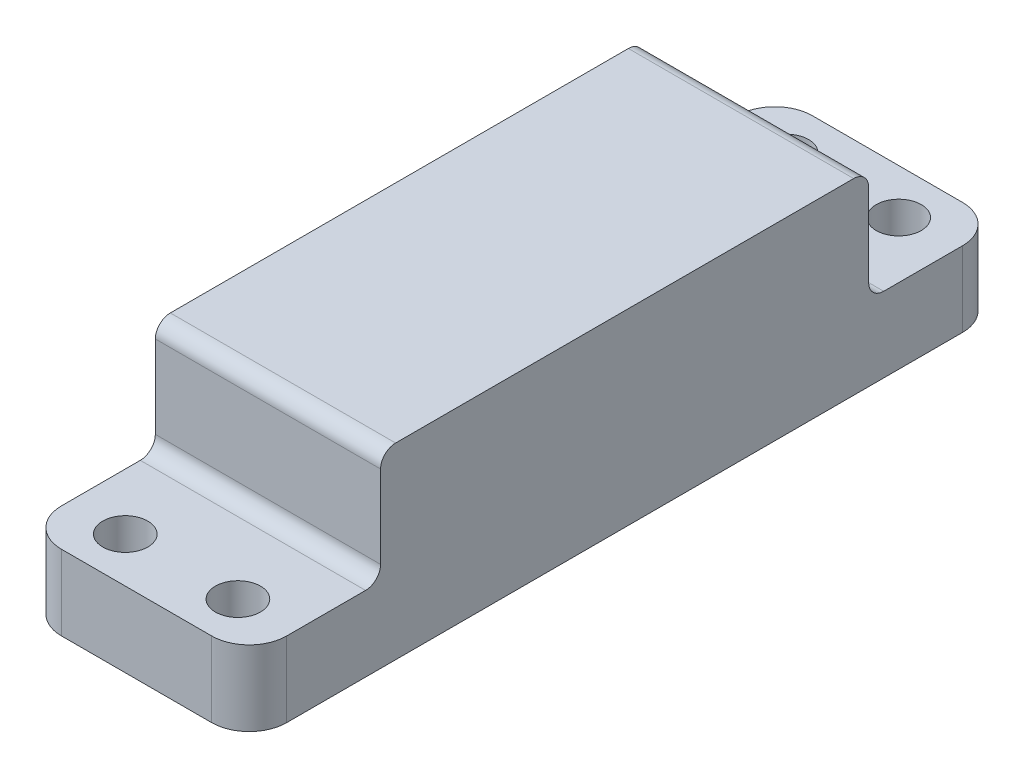
SolidWorks part; units mm, degrees
ref_plane "Front Plane" through (0, 0, 0) normal (0, 0, 1) x (1, 0, 0)
ref_plane "Top Plane" through (0, 0, 0) normal (0, 1, 0) x (1, 0, 0)
ref_plane "Right Plane" through (0, 0, 0) normal (1, 0, 0) x (0, 0, -1)
sketch "Sketch1" plane through (0, 0, 0) normal (1, 0, 0) x (0, 0, -1)
  line L0 (0, 0) -> (0, 50) construction
  line L1 (100, 0) -> (-100, 0)
  line L2 (-100, 0) -> (-100, 20)
  line L3 (100, 0) -> (100, 20)
  line L4 (-100, 20) -> (-69, 20)
  line L5 (100, 20) -> (69, 20)
  line L6 (-65, 24) -> (-65, 46)
  line L7 (65, 24) -> (65, 46)
  line L8 (-61, 50) -> (61, 50)
  arc A0 (-69, 20) -> (-65, 24) centre (-69, 24) ccw
  arc A1 (69, 20) -> (65, 24) centre (69, 24) cw
  arc A2 (-65, 46) -> (-61, 50) centre (-61, 46) cw
  arc A3 (65, 46) -> (61, 50) centre (61, 46) ccw
  point P17 (-100, 10)
  dimension "D2" = 4
  dimension "D1" = 200
  dimension "D3" = 35
  dimension "D4" = 50
  dimension "D5" = 20
extrude "Boss-Extrude1" add sketch "Sketch1" along normal mid plane 60
fillet "Fillet1" radius 10 4 edges at (-30, 10, 100) (30, 10, -100) (-30, 10, -100) (30, 10, 100)
sketch "Sketch4" plane through (0, 20, 0) normal (0, 1, 0) x (1, 0, 0)
  line L0 (-30, -69) -> (-30, -90) construction
  line L1 (20, -100) -> (-20, -100) construction
  line L2 (20, 100) -> (-20, 100) construction
  line L3 (-30, 90) -> (-30, 69) construction
  point P0 (-15, -88)
  point P2 (15, -88)
  point P4 (15, 88)
  point P6 (-15, 88)
  dimension "D1" = 15
  dimension "D2" = 30
  dimension "D3" = 12
  dimension "D4" = 12
  dimension "D5" = 15
  dimension "D6" = 30
hole_wizard "CBORE for M12 Hex Head Bolt1" positions "Sketch4" profile "Sketch3" counterbore size "M12" standard "DIN" end condition through all
sketch "Sketch3" plane through (-15, 20, 88) normal (1, 0, 0) x (0, 0, 1)
  line L0 (0, 0) -> (0, 20)
  line L1 (0, 20) -> (4, 20)
  line L3 (4, 20) -> (4, 10)
  line L4 (4, 10) -> (6, 10)
  line L5 (6, 10) -> (6, 0)
  line L7 (6, 0) -> (0, 0)
  line L11 (0, -6.35) -> (0, 107.95) construction
  dimension "Thru Hole Dia." = 8
  dimension "Thru Hole Depth" = 20
  dimension "C'Bore Dia." = 12
  dimension "C'Bore Depth" = 10
